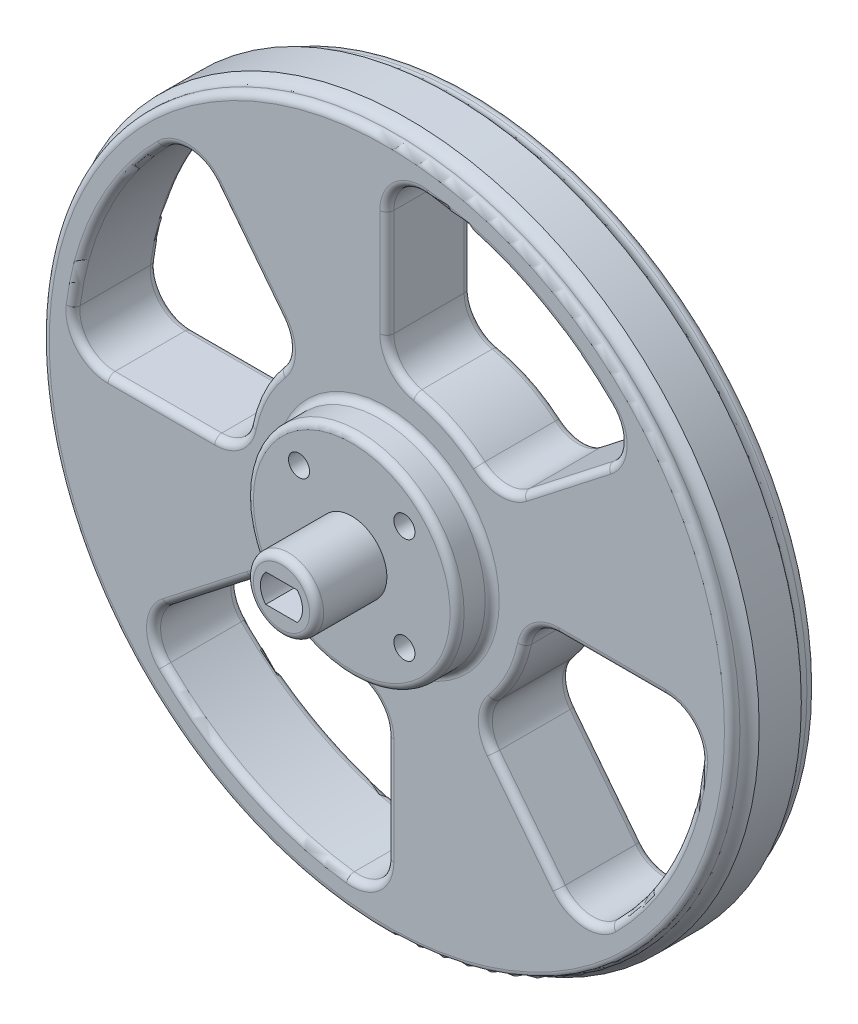
SolidWorks part; units mm, degrees
ref_plane "Alzado" through (0, 0, 0) normal (0, 0, 1) x (1, 0, 0)
ref_plane "Planta" through (0, 0, 0) normal (0, 1, 0) x (1, 0, 0)
ref_plane "Vista lateral" through (0, 0, 0) normal (1, 0, 0) x (0, 0, -1)
sketch "Croquis1" plane through (0, 0, 0) normal (0, 0, 1) x (1, 0, 0)
  line L0 (-7.3928, 0) -> (5.9139, 0) construction
  line L1 (-2.2361, -2) -> (2.2361, -2)
  line L2 (-2.2361, 2) -> (2.2361, 2)
  line L3 (-7.3928, 2) -> (5.9139, 2) construction
  line L4 (-7.3928, -2) -> (5.9139, -2) construction
  arc A0 (-2.2361, 2) -> (-2.2361, -2) centre (0, 0) ccw
  arc A1 (2.2361, -2) -> (2.2361, 2) centre (0, 0) ccw
  circle A2 centre (0, 0) radius 5
  dimension "D1" = 6
  dimension "D4" = 10
  dimension "D2" = 2
  dimension "D3" = 2
extrude "Saliente-Extruir1" add sketch "Croquis1" along normal mid plane 10
sketch "Croquis2" plane through (0, 0, -5) normal (0, 0, -1) x (-1, 0, 0)
  circle A0 centre (0, 0) radius 15
  dimension "D1" = 30
extrude "Saliente-Extruir2" add sketch "Croquis2" along normal blind 5
sketch "Croquis3" plane through (0, 0, -5) normal (0, 0, 1) x (1, 0, 0)
  line L1 (-7.5, -7.5) -> (7.5, -7.5) construction
  line L2 (-7.5, -7.5) -> (-7.5, 7.5) construction
  line L3 (-7.5, 7.5) -> (7.5, 7.5) construction
  line L4 (7.5, -7.5) -> (7.5, 7.5) construction
  line L5 (-7.5, -7.5) -> (7.5, 7.5) construction
  line L6 (-7.5, 7.5) -> (7.5, -7.5) construction
  circle A0 centre (-7.5, 7.5) radius 1.5
  circle A1 centre (7.5, 7.5) radius 1.5
  circle A2 centre (-7.5, -7.5) radius 1.5
  circle A3 centre (7.5, -7.5) radius 1.5
  point P0 (0, 0)
  dimension "D3" = 3
  dimension "D1" = 15
  dimension "D2" = 15
extrude "Cortar-Extruir1" cut sketch "Croquis3" against normal blind 5 contours A3 | A2 | A1 | A0
fillet "Redondeo1" radius 1 1 edges at (-15, 0, -5)
fillet "Redondeo2" radius 1 1 edges at (5, 0, 5)
sketch "Croquis5" plane through (0, 0, 0) normal (0, 1, 0) x (1, 0, 0)
  line L0 (0, 0) -> (0, 10) construction
  line L1 (15, 10) -> (-15, 10) construction
  line L2 (0, 10) -> (50, 10)
  line L3 (50, 10) -> (50, 22) construction
  line L4 (50, 16) -> (-31.2563, 16) construction
  line L5 (50, 13) -> (50, 19)
  line L6 (49, 11) -> (49, 22) construction
  line L7 (50, 20.5) -> (-31.2563, 20.5) construction
  line L8 (50, 11.5) -> (-31.2563, 11.5) construction
  line L9 (50, 22) -> (0, 22)
  line L10 (0, 22) -> (0, 10)
  line L11 (0, 10) -> (-0.0366, 10.4645)
  line L14 (0, 11) -> (49, 11) construction
  spline S0 degree 2 poles (50, 10) (48, 11.5) (50, 13) knots 0 0 0 1 1 1
  spline S1 degree 2 poles (50, 19) (48, 20.5) (50, 22) knots 0 0 0 1 1 1
  dimension "D1" = 50
  dimension "D2" = 12
  dimension "D4" = 6
  dimension "D5" = 3
  dimension "D3" = 1
  dimension "D6" = 4.5
  dimension "D7" = 4.5
revolve "Revolución1" add sketch "Croquis5" angle 360 about L0
sketch "Croquis6" plane through (0, 0, -10) normal (0, 0, 1) x (1, 0, 0)
  line L0 (0, 0) -> (0, 52.8836) construction
  line L1 (0, 24.4949) -> (0, 39.6863)
  line L2 (19.3101, 15.0705) -> (31.286, 24.4169)
  line L3 (0, 0) -> (52.8836, 0) construction
  line L4 (15.0705, -19.3101) -> (24.4169, -31.286)
  line L5 (24.4949, 0) -> (39.6863, 0)
  line L6 (0, 0) -> (0, -52.8836) construction
  line L7 (-19.3101, -15.0705) -> (-31.286, -24.4169)
  line L8 (0, -24.4949) -> (0, -39.6863)
  line L9 (0, 0) -> (-52.8836, 0) construction
  line L10 (-15.0705, 19.3101) -> (-24.4169, 31.286)
  line L11 (-24.4949, 0) -> (-39.6863, 0)
  arc A0 (12.9871, 15.2097) -> (4, 19.5959) centre (0, 0) ccw
  arc A1 (31.736, 31.9034) -> (5.625, 44.6471) centre (0, 0) ccw
  arc A2 (31.736, 31.9034) -> (31.286, 24.4169) centre (28.2097, 28.3586) cw
  arc A3 (19.3101, 15.0705) -> (12.9871, 15.2097) centre (16.2339, 19.0121) cw
  arc A4 (4, 19.5959) -> (0, 24.4949) centre (5, 24.4949) cw
  arc A5 (5.625, 44.6471) -> (0, 39.6863) centre (5, 39.6863) ccw
  arc A6 (31.9034, -31.736) -> (24.4169, -31.286) centre (28.3586, -28.2097) cw
  arc A7 (31.9034, -31.736) -> (44.6471, -5.625) centre (0, 0) ccw
  arc A8 (44.6471, -5.625) -> (39.6863, 0) centre (39.6863, -5) ccw
  arc A9 (19.5959, -4) -> (24.4949, 0) centre (24.4949, -5) cw
  arc A10 (15.2097, -12.9871) -> (19.5959, -4) centre (0, 0) ccw
  arc A11 (15.0705, -19.3101) -> (15.2097, -12.9871) centre (19.0121, -16.2339) cw
  arc A12 (-31.736, -31.9034) -> (-31.286, -24.4169) centre (-28.2097, -28.3586) cw
  arc A13 (-31.736, -31.9034) -> (-5.625, -44.6471) centre (0, 0) ccw
  arc A14 (-5.625, -44.6471) -> (0, -39.6863) centre (-5, -39.6863) ccw
  arc A15 (-4, -19.5959) -> (0, -24.4949) centre (-5, -24.4949) cw
  arc A16 (-12.9871, -15.2097) -> (-4, -19.5959) centre (0, 0) ccw
  arc A17 (-19.3101, -15.0705) -> (-12.9871, -15.2097) centre (-16.2339, -19.0121) cw
  arc A18 (-31.9034, 31.736) -> (-24.4169, 31.286) centre (-28.3586, 28.2097) cw
  arc A19 (-31.9034, 31.736) -> (-44.6471, 5.625) centre (0, 0) ccw
  arc A20 (-44.6471, 5.625) -> (-39.6863, 0) centre (-39.6863, 5) ccw
  arc A21 (-19.5959, 4) -> (-24.4949, 0) centre (-24.4949, 5) cw
  arc A22 (-15.2097, 12.9871) -> (-19.5959, 4) centre (0, 0) ccw
  arc A23 (-15.0705, 19.3101) -> (-15.2097, 12.9871) centre (-19.0121, 16.2339) cw
  point P13 (0, 20)
  point P16 (0, 45)
  point P59 (0, 0)
  dimension "D1" = 40
  dimension "D2" = 90
  dimension "D3" = 5
  dimension "D4" = 4
extrude "Cortar-Extruir2" cut sketch "Croquis6" against normal through all
fillet "Redondeo3" radius 1 67 edges at (50, 0, -22) (25.2981, 19.7437, -22) (16.1238, 14.0133, -22) (8.7721, 17.9736, -22) (1.127, 21.3326, -22) (0, 32.0906, -22) (1.6928, 43.4363, -22) (19.7373, 40.4406, -22) (33.2007, 28.0586, -22) (28.0586, -33.2007, -22) (19.7437, -25.2981, -22) (14.0133, -16.1238, -22) (17.9736, -8.7721, -22) (21.3326, -1.127, -22) (32.0906, 0, -22) (43.4363, -1.6928, -22) (40.4406, -19.7373, -22) (-33.2007, -28.0586, -22) (-25.2981, -19.7437, -22) (-16.1238, -14.0133, -22) (-8.7721, -17.9736, -22) (-1.127, -21.3326, -22) (0, -32.0906, -22) (-1.6928, -43.4363, -22) (-19.7373, -40.4406, -22) (-28.0586, 33.2007, -22) (-19.7437, 25.2981, -22) (-14.0133, 16.1238, -22) (-17.9736, 8.7721, -22) (-21.3326, 1.127, -22) (-32.0906, 0, -22) (-43.4363, 1.6928, -22) (-40.4406, 19.7373, -22) (-15, 0, -10) (50, 0, -10) (19.7373, 40.4406, -10) (1.6928, 43.4363, -10) (0, 32.0906, -10) (1.127, 21.3326, -10) (8.7721, 17.9736, -10) (16.1238, 14.0133, -10) (25.2981, 19.7437, -10) (33.2007, 28.0586, -10) (43.4363, -1.6928, -10) (32.0906, 0, -10) (21.3326, -1.127, -10) (17.9736, -8.7721, -10) (14.0133, -16.1238, -10) (19.7437, -25.2981, -10) (28.0586, -33.2007, -10) (40.4406, -19.7373, -10) (-1.6928, -43.4363, -10) (0, -32.0906, -10) (-1.127, -21.3326, -10) (-8.7721, -17.9736, -10) (-16.1238, -14.0133, -10) (-25.2981, -19.7437, -10) (-33.2007, -28.0586, -10) (-19.7373, -40.4406, -10) (-43.4363, 1.6928, -10) (-32.0906, 0, -10) (-21.3326, 1.127, -10) (-17.9736, 8.7721, -10) (-14.0133, 16.1238, -10) (-19.7437, 25.2981, -10) (-28.0586, 33.2007, -10) (-40.4406, 19.7373, -10)
sketch "Croquis7" plane through (0, 0, -22) normal (0, 0, -1) x (-1, 0, 0)
  text T0 "TEC." font "Comic Sans MS" height in points 18
  text T1 "N°5" font "Comic Sans MS" height in points 18
extrude "Cortar-Extruir4" cut sketch "Croquis7" against normal blind 3
